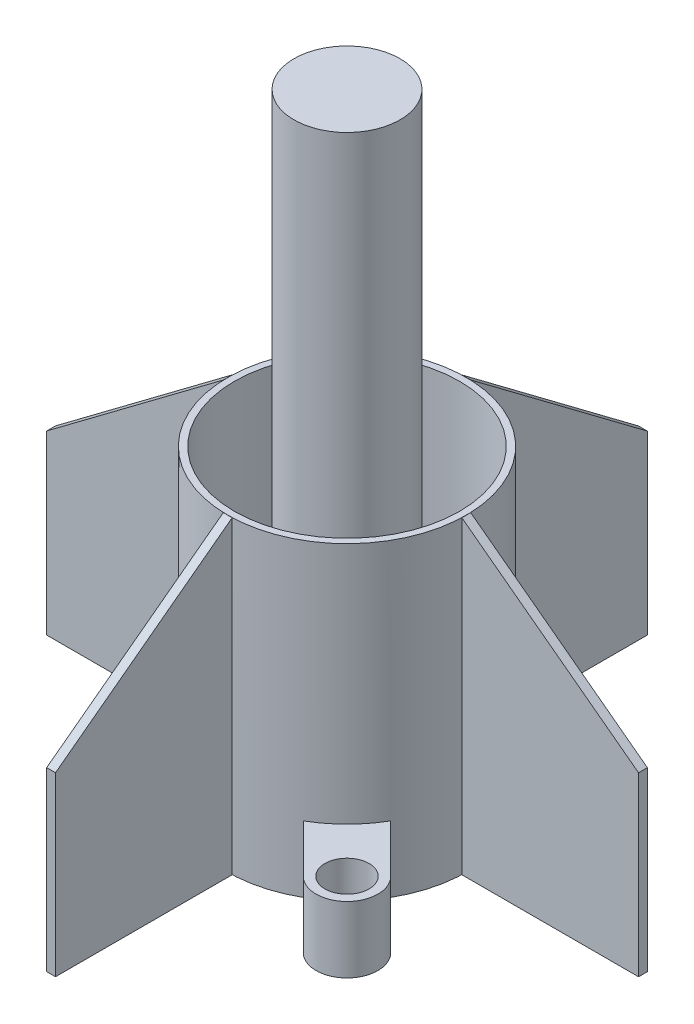
SolidWorks part; units mm, degrees
ref_plane "Front Plane" through (0, 0, 0) normal (0, 0, 1) x (1, 0, 0)
ref_plane "Top Plane" through (0, 0, 0) normal (0, 1, 0) x (1, 0, 0)
ref_plane "Right Plane" through (0, 0, 0) normal (1, 0, 0) x (0, 0, -1)
sketch "Sketch1" plane through (0, 0, 0) normal (0, 1, 0) x (1, 0, 0)
  circle A0 centre (0, 0) radius 27
  dimension "D1" = 54
extrude "Boss-Extrude1" add sketch "Sketch1" along normal blind 70
sketch "Sketch2" plane through (0, 0, 0) normal (0, 0, 1) x (1, 0, 0)
  line L0 (27, 70) -> (67, 40)
  line L1 (67, 40) -> (67, 0)
  line L2 (67, 0) -> (27, 0)
  line L3 (27, 0) -> (27, 70)
  line L4 (0, -55) -> (0, 55) construction
  line L5 (-67, 0) -> (-27, 0)
  line L6 (-67, 40) -> (-67, 0)
  line L7 (-27, 70) -> (-67, 40)
  line L8 (-27, 0) -> (-27, 70)
  dimension "D1" = 40
  dimension "D2" = 40
extrude "Boss-Extrude2" add sketch "Sketch2" along normal mid plane 2 separate body
sketch "Sketch3" plane through (0, 0, 0) normal (1, 0, 0) x (0, 0, -1)
  line L0 (-27, 70) -> (-66.9853, 40)
  line L1 (-66.9853, 40) -> (-66.9853, 0)
  line L2 (-66.9853, 0) -> (-27, 0)
  line L3 (-27, 0) -> (-27, 70)
  line L4 (0, 55) -> (0, -55) construction
  line L5 (27, 0) -> (27, 70)
  line L6 (66.9853, 0) -> (27, 0)
  line L7 (66.9853, 40) -> (66.9853, 0)
  line L8 (27, 70) -> (66.9853, 40)
  dimension "D1" = 39.9853
  dimension "D2" = 40
extrude "Boss-Extrude3" add sketch "Sketch3" along normal mid plane 2 separate body
sketch "Sketch4" plane through (0, 0, 0) normal (0, -1, 0) x (-1, 0, 0)
  circle A0 centre (0, 0) radius 25.5
  dimension "D1" = 51
extrude "Cut-Extrude1" cut sketch "Sketch4" against normal through all
sketch "Sketch9" plane through (0, 0, 0) normal (0, -1, 0) x (1, 0, 0)
  circle A0 centre (0, 0) radius 27
extrude "Boss-Extrude6" add sketch "Sketch9" against normal blind 4
sketch "Sketch10" plane through (0, 0, 0) normal (0, -1, 0) x (1, 0, 0)
  circle A0 centre (0, 0) radius 12
  dimension "D1" = 24
extrude "Boss-Extrude7" add sketch "Sketch10" against normal blind 140
sketch "Sketch11" plane through (0, 0, 0) normal (0, -1, 0) x (1, 0, 0)
  circle A0 centre (0, 0) radius 10.5
  dimension "D1" = 21
extrude "Cut-Extrude3" cut sketch "Sketch11" against normal blind 125
fillet "Fillet1" radius 10 1 edges at (0, 4, -12)
sketch "Sketch13" plane through (0, 0, 0) normal (0, -1, 0) x (1, 0, 0)
  line L0 (0, 0) -> (50.3848, 50.3848) construction
  line L1 (27, 1) -> (67, 1) construction
  line L2 (13.4893, 23.3888) -> (24.3334, 34.2328)
  line L3 (23.3888, 13.4893) -> (34.2328, 24.3334)
  line L4 (13.4893, 23.3888) -> (23.3888, 13.4893)
  line L5 (-49.4055, 49.4055) -> (49.4055, -49.4055) construction
  line L6 (-23.3888, -13.4893) -> (-34.2328, -24.3334)
  line L7 (-23.3888, -13.4893) -> (-13.4893, -23.3888)
  line L8 (-13.4893, -23.3888) -> (-24.3334, -34.2328)
  circle A0 centre (0, 0) radius 27 construction
  arc A1 (24.3334, 34.2328) -> (34.2328, 24.3334) centre (29.2831, 29.2831) cw
  arc A2 (-34.2328, -24.3334) -> (-24.3334, -34.2328) centre (-29.2831, -29.2831) ccw
  point P9 (18.4391, 18.4391)
  point P15 (0, 0)
  dimension "D1" = 45
  dimension "D2" = 14
  dimension "D3" = 42
extrude "Boss-Extrude8" add sketch "Sketch13" against normal blind 15
sketch "Sketch14" plane through (0, 0, 0) normal (0, -1, 0) x (1, 0, 0)
  line L0 (0, 0) -> (51.3613, -51.3613) construction
  line L1 (1, -27) -> (1, -66.9853) construction
  line L2 (34.2328, 24.3334) -> (24.3334, 34.2328) construction
  circle A0 centre (29.2831, 29.2831) radius 5
  circle A1 centre (-29.2831, -29.2831) radius 5
  point P14 (29.2831, 29.2831)
  dimension "D2" = 10
  dimension "D1" = 45
extrude "Cut-Extrude4" cut sketch "Sketch14" against normal up to surface (15 mm away) up to face at (25.2617, 15, 25.2617)
